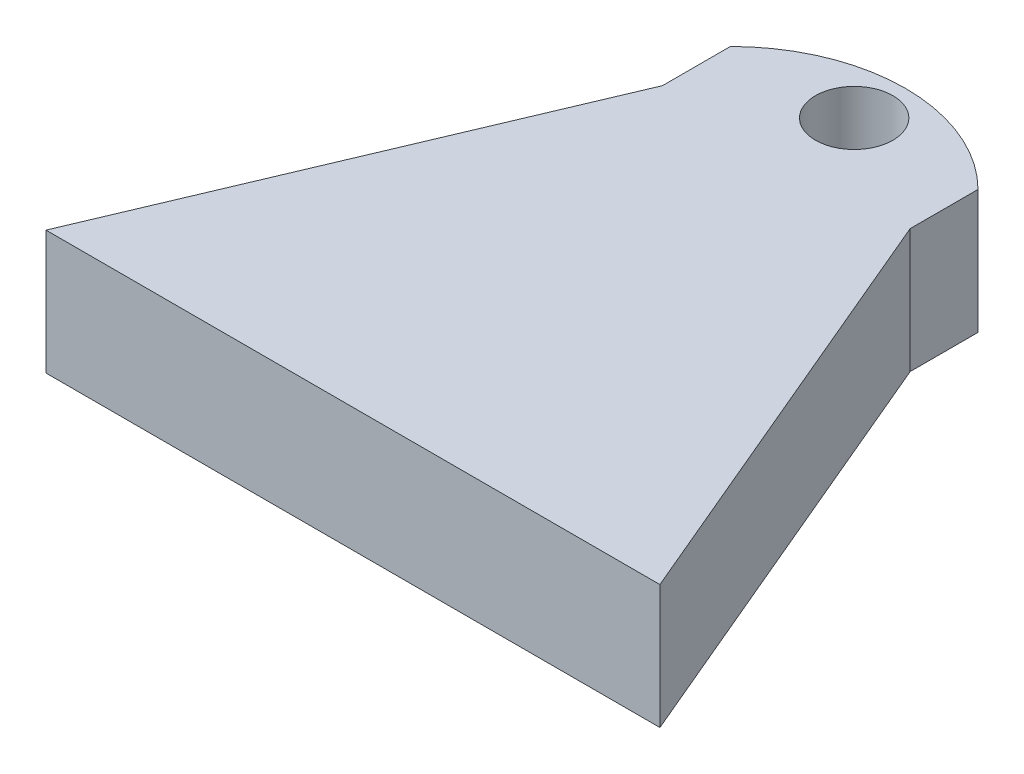
SolidWorks part; units mm, degrees
ref_plane "Front Plane" through (0, 0, 0) normal (0, 0, 1) x (1, 0, 0)
ref_plane "Top Plane" through (0, 0, 0) normal (0, 1, 0) x (1, 0, 0)
ref_plane "Right Plane" through (0, 0, 0) normal (1, 0, 0) x (0, 0, -1)
sketch "Sketch1" plane through (0, 0, 0) normal (0, 1, 0) x (1, 0, 0)
  line L3 (0, 0) -> (125.9336, 0)
  line L6 (62.9668, 0) -> (62.9668, 94.8788) construction
  line L7 (62.9668, 88.9) -> (37.5668, 88.9) construction
  line L8 (62.9668, 88.9) -> (88.3668, 88.9) construction
  line L9 (0, 0) -> (37.5668, 88.9)
  line L10 (125.9336, 0) -> (88.3668, 88.9)
  line L11 (37.5668, 88.9) -> (37.5668, 102.8163)
  line L12 (37.5668, 102.8163) -> (55.0293, 102.8163) construction
  line L13 (88.3668, 88.9) -> (88.3668, 102.8163)
  line L14 (70.9043, 102.8163) -> (88.3668, 102.8163) construction
  line L15 (62.9668, 88.9) -> (62.9668, 102.8163) construction
  circle A2 centre (62.9668, 102.8163) radius 7.9375
  arc A3 (37.5668, 102.8163) -> (88.3668, 102.8163) centre (62.9668, 77.4163) cw
  dimension "D4" = 15.875
  dimension "D1" = 88.9
  dimension "D2" = 25.4
  dimension "D3" = 25.4
extrude "Boss-Extrude1" add sketch "Sketch1" along normal blind 25.4
